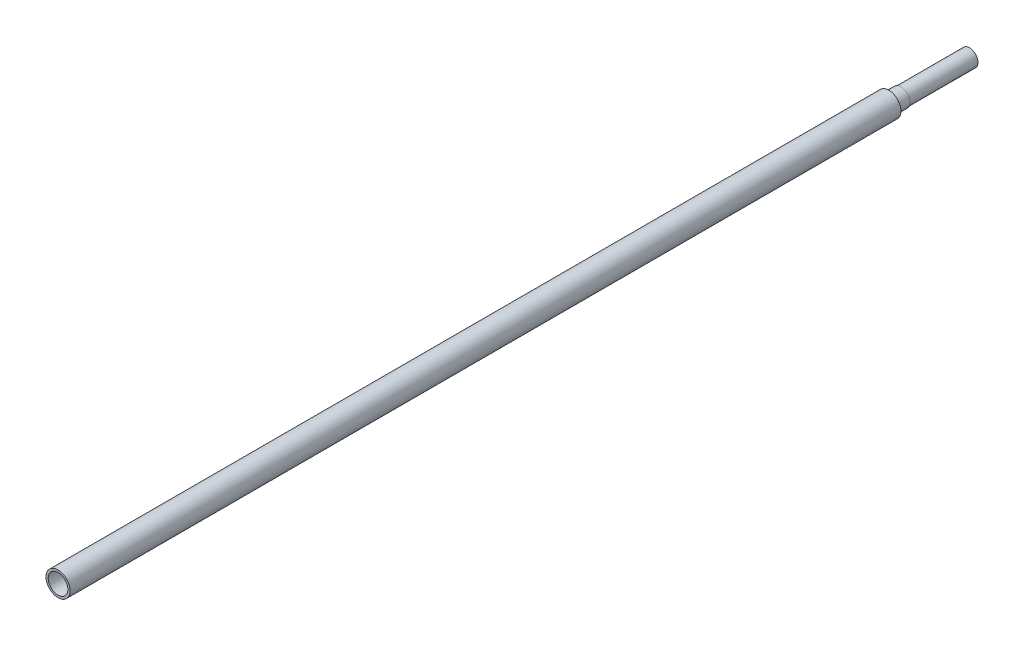
SolidWorks part; units mm, degrees
ref_plane "前视基准面" through (0, 0, 0) normal (0, 0, 1) x (1, 0, 0)
ref_plane "上视基准面" through (0, 0, 0) normal (0, 1, 0) x (1, 0, 0)
ref_plane "右视基准面" through (0, 0, 0) normal (1, 0, 0) x (0, 0, -1)
sketch "草图1" plane through (0, 0, 0) normal (0, 0, 1) x (1, 0, 0)
  circle A0 centre (0, 0) radius 7
extrude "凸台-拉伸1" add sketch "草图1" along normal blind 57
sketch "草图2" plane through (0, 0, 57) normal (0, 0, 1) x (1, 0, 0)
  circle A0 centre (0, 0) radius 7.5
  dimension "D1" = 15
extrude "凸台-拉伸2" add sketch "草图2" along normal blind 10
sketch "草图3" plane through (0, 0, 67) normal (0, 0, 1) x (1, 0, 0)
  circle A0 centre (0, 0) radius 10
extrude "凸台-拉伸3" add sketch "草图3" along normal blind 690
sketch "草图4" plane through (0, 0, 0) normal (1, 0, 0) x (0, 0, -1)
  line L0 (-772.3934, 0) -> (-751.4174, 0) construction
  line L1 (-757, 0) -> (-757, 5)
  line L2 (-757, 10) -> (-757, -10) construction
  line L3 (-757, 5) -> (-761.4923, 8.1456)
  line L4 (-761.4923, 8.1456) -> (-738.3043, 8.1456)
  line L5 (-738.3043, 8.1456) -> (-733.6015, 0)
  line L6 (-733.6015, 0) -> (-757, 0)
  dimension "D1" = 60
  dimension "D2" = 145
  dimension "D3" = 5
  dimension "D4" = 23.188
revolve "切除-旋转1" cut sketch "草图4" angle 360 about L0
